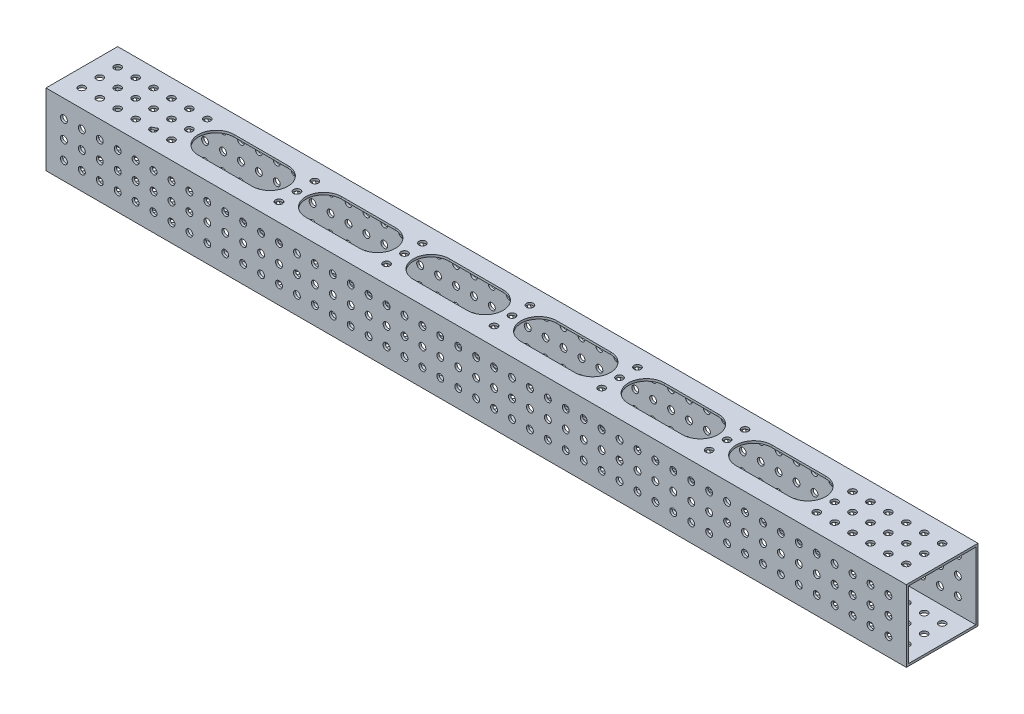
SolidWorks part; units mm, degrees
ref_plane "Front Plane" through (0, 0, 0) normal (0, 0, 1) x (1, 0, 0)
ref_plane "Top Plane" through (0, 0, 0) normal (0, 1, 0) x (1, 0, 0)
ref_plane "Right Plane" through (0, 0, 0) normal (1, 0, 0) x (0, 0, -1)
sketch "Sketch1" plane through (0, 0, 0) normal (1, 0, 0) x (0, 0, -1)
  line L1 (-25.4, -25.4) -> (25.4, -25.4)
  line L2 (-25.4, -25.4) -> (-25.4, 25.4)
  line L3 (-25.4, 25.4) -> (25.4, 25.4)
  line L4 (25.4, -25.4) -> (25.4, 25.4)
  line L5 (-25.4, -25.4) -> (25.4, 25.4) construction
  line L6 (-25.4, 25.4) -> (25.4, -25.4) construction
  line L7 (-23.8125, -23.8125) -> (23.8125, -23.8125)
  line L8 (-23.8125, -23.8125) -> (-23.8125, 23.8125)
  line L9 (-23.8125, 23.8125) -> (23.8125, 23.8125)
  line L10 (23.8125, -23.8125) -> (23.8125, 23.8125)
  line L11 (-23.8125, -23.8125) -> (23.8125, 23.8125) construction
  line L12 (-23.8125, 23.8125) -> (23.8125, -23.8125) construction
  point P0 (0, 0)
  point P7 (0, 0)
  dimension "D1" = 50.8
  dimension "D2" = 50.8
  dimension "D3" = 47.625
extrude "Boss-Extrude1" add sketch "Sketch1" along normal blind 609.6
sketch "Sketch2" plane through (0, 0, 25.4) normal (0, 0, 1) x (1, 0, 0)
  line L0 (-1000, 0) -> (49000, 0) construction
  line L2 (-994.1549, 12.7) -> (49005.8451, 12.7) construction
  line L3 (-984.8446, -12.7) -> (49015.1554, -12.7) construction
  line L4 (609.6, 25.4) -> (0, 25.4) construction
  line L5 (609.6, -25.4) -> (0, -25.4) construction
  line L6 (0, 25.4) -> (0, -25.4) construction
  line L7 (12.7, 12.7) -> (12.7, 0) construction
  line L8 (12.7, 12.7) -> (25.4, 12.7) construction
  circle A24 centre (12.7, 12.7) radius 2.4384
  circle A25 centre (12.7, 0) radius 2.4384
  circle A26 centre (12.7, -12.7) radius 2.4384
  circle A27 centre (25.4, 12.7) radius 2.4384
  circle A28 centre (25.4, 0) radius 2.4384
  circle A29 centre (25.4, -12.7) radius 2.4384
  circle A30 centre (38.1, 12.7) radius 2.4384
  circle A31 centre (38.1, 0) radius 2.4384
  circle A32 centre (38.1, -12.7) radius 2.4384
  circle A33 centre (50.8, 12.7) radius 2.4384
  circle A34 centre (50.8, 0) radius 2.4384
  circle A35 centre (50.8, -12.7) radius 2.4384
  circle A36 centre (63.5, 12.7) radius 2.4384
  circle A37 centre (63.5, 0) radius 2.4384
  circle A38 centre (63.5, -12.7) radius 2.4384
  circle A39 centre (76.2, 12.7) radius 2.4384
  circle A40 centre (76.2, 0) radius 2.4384
  circle A41 centre (76.2, -12.7) radius 2.4384
  circle A42 centre (88.9, 12.7) radius 2.4384
  circle A43 centre (88.9, 0) radius 2.4384
  circle A44 centre (88.9, -12.7) radius 2.4384
  circle A45 centre (101.6, 12.7) radius 2.4384
  circle A46 centre (101.6, 0) radius 2.4384
  circle A47 centre (101.6, -12.7) radius 2.4384
  circle A48 centre (114.3, 12.7) radius 2.4384
  circle A49 centre (114.3, 0) radius 2.4384
  circle A50 centre (114.3, -12.7) radius 2.4384
  circle A51 centre (127, 12.7) radius 2.4384
  circle A52 centre (127, 0) radius 2.4384
  circle A53 centre (127, -12.7) radius 2.4384
  circle A54 centre (139.7, 12.7) radius 2.4384
  circle A55 centre (139.7, 0) radius 2.4384
  circle A56 centre (139.7, -12.7) radius 2.4384
  circle A57 centre (152.4, 12.7) radius 2.4384
  circle A58 centre (152.4, 0) radius 2.4384
  circle A59 centre (152.4, -12.7) radius 2.4384
  circle A60 centre (165.1, 12.7) radius 2.4384
  circle A61 centre (165.1, 0) radius 2.4384
  circle A62 centre (165.1, -12.7) radius 2.4384
  circle A63 centre (177.8, 12.7) radius 2.4384
  circle A64 centre (177.8, 0) radius 2.4384
  circle A65 centre (177.8, -12.7) radius 2.4384
  circle A66 centre (190.5, 12.7) radius 2.4384
  circle A67 centre (190.5, 0) radius 2.4384
  circle A68 centre (190.5, -12.7) radius 2.4384
  circle A69 centre (203.2, 12.7) radius 2.4384
  circle A70 centre (203.2, 0) radius 2.4384
  circle A71 centre (203.2, -12.7) radius 2.4384
  circle A72 centre (215.9, 12.7) radius 2.4384
  circle A73 centre (215.9, 0) radius 2.4384
  circle A74 centre (215.9, -12.7) radius 2.4384
  circle A75 centre (228.6, 12.7) radius 2.4384
  circle A76 centre (228.6, 0) radius 2.4384
  circle A77 centre (228.6, -12.7) radius 2.4384
  circle A78 centre (241.3, 12.7) radius 2.4384
  circle A79 centre (241.3, 0) radius 2.4384
  circle A80 centre (241.3, -12.7) radius 2.4384
  circle A81 centre (254, 12.7) radius 2.4384
  circle A82 centre (254, 0) radius 2.4384
  circle A83 centre (254, -12.7) radius 2.4384
  circle A84 centre (266.7, 12.7) radius 2.4384
  circle A85 centre (266.7, 0) radius 2.4384
  circle A86 centre (266.7, -12.7) radius 2.4384
  circle A87 centre (279.4, 12.7) radius 2.4384
  circle A88 centre (279.4, 0) radius 2.4384
  circle A89 centre (279.4, -12.7) radius 2.4384
  circle A90 centre (292.1, 12.7) radius 2.4384
  circle A91 centre (292.1, 0) radius 2.4384
  circle A92 centre (292.1, -12.7) radius 2.4384
  circle A93 centre (304.8, 12.7) radius 2.4384
  circle A94 centre (304.8, 0) radius 2.4384
  circle A95 centre (304.8, -12.7) radius 2.4384
  circle A96 centre (317.5, 12.7) radius 2.4384
  circle A97 centre (317.5, 0) radius 2.4384
  circle A98 centre (317.5, -12.7) radius 2.4384
  circle A99 centre (330.2, 12.7) radius 2.4384
  circle A100 centre (330.2, 0) radius 2.4384
  circle A101 centre (330.2, -12.7) radius 2.4384
  circle A102 centre (342.9, 12.7) radius 2.4384
  circle A103 centre (342.9, 0) radius 2.4384
  circle A104 centre (342.9, -12.7) radius 2.4384
  circle A105 centre (355.6, 12.7) radius 2.4384
  circle A106 centre (355.6, 0) radius 2.4384
  circle A107 centre (355.6, -12.7) radius 2.4384
  circle A108 centre (368.3, 12.7) radius 2.4384
  circle A109 centre (368.3, 0) radius 2.4384
  circle A110 centre (368.3, -12.7) radius 2.4384
  circle A111 centre (381, 12.7) radius 2.4384
  circle A112 centre (381, 0) radius 2.4384
  circle A113 centre (381, -12.7) radius 2.4384
  circle A114 centre (393.7, 12.7) radius 2.4384
  circle A115 centre (393.7, 0) radius 2.4384
  circle A116 centre (393.7, -12.7) radius 2.4384
  circle A117 centre (406.4, 12.7) radius 2.4384
  circle A118 centre (406.4, 0) radius 2.4384
  circle A119 centre (406.4, -12.7) radius 2.4384
  circle A120 centre (419.1, 12.7) radius 2.4384
  circle A121 centre (419.1, 0) radius 2.4384
  circle A122 centre (419.1, -12.7) radius 2.4384
  circle A123 centre (431.8, 12.7) radius 2.4384
  circle A124 centre (431.8, 0) radius 2.4384
  circle A125 centre (431.8, -12.7) radius 2.4384
  circle A126 centre (444.5, 12.7) radius 2.4384
  circle A127 centre (444.5, 0) radius 2.4384
  circle A128 centre (444.5, -12.7) radius 2.4384
  circle A129 centre (457.2, 12.7) radius 2.4384
  circle A130 centre (457.2, 0) radius 2.4384
  circle A131 centre (457.2, -12.7) radius 2.4384
  circle A132 centre (469.9, 12.7) radius 2.4384
  circle A133 centre (469.9, 0) radius 2.4384
  circle A134 centre (469.9, -12.7) radius 2.4384
  circle A135 centre (482.6, 12.7) radius 2.4384
  circle A136 centre (482.6, 0) radius 2.4384
  circle A137 centre (482.6, -12.7) radius 2.4384
  circle A138 centre (495.3, 12.7) radius 2.4384
  circle A139 centre (495.3, 0) radius 2.4384
  circle A140 centre (495.3, -12.7) radius 2.4384
  circle A141 centre (508, 12.7) radius 2.4384
  circle A142 centre (508, 0) radius 2.4384
  circle A143 centre (508, -12.7) radius 2.4384
  circle A144 centre (520.7, 12.7) radius 2.4384
  circle A145 centre (520.7, 0) radius 2.4384
  circle A146 centre (520.7, -12.7) radius 2.4384
  circle A147 centre (533.4, 12.7) radius 2.4384
  circle A148 centre (533.4, 0) radius 2.4384
  circle A149 centre (533.4, -12.7) radius 2.4384
  circle A150 centre (546.1, 12.7) radius 2.4384
  circle A151 centre (546.1, 0) radius 2.4384
  circle A152 centre (546.1, -12.7) radius 2.4384
  circle A153 centre (558.8, 12.7) radius 2.4384
  circle A154 centre (558.8, 0) radius 2.4384
  circle A155 centre (558.8, -12.7) radius 2.4384
  circle A156 centre (571.5, 12.7) radius 2.4384
  circle A157 centre (571.5, 0) radius 2.4384
  circle A158 centre (571.5, -12.7) radius 2.4384
  circle A159 centre (584.2, 12.7) radius 2.4384
  circle A160 centre (584.2, 0) radius 2.4384
  circle A161 centre (584.2, -12.7) radius 2.4384
  circle A162 centre (596.9, 12.7) radius 2.4384
  circle A163 centre (596.9, 0) radius 2.4384
  circle A164 centre (596.9, -12.7) radius 2.4384
  dimension "D1" = 12.7
  dimension "D3" = 4.8768
  dimension "D2" = 12.7
  dimension "D4" = 12.7
  dimension "D6" = 12.7
  dimension "D8" = 12.7
  dimension "D5" = 3
  dimension "D7" = 47
extrude "Cut-Extrude2" cut sketch "Sketch2" against normal blind 609.6
sketch "Sketch3" plane through (0, -25.4, 0) normal (0, -1, 0) x (1, 0, 0)
  line L0 (0, 0) -> (6.35, 0)
  line L1 (76.2, 12.7) -> (63.5, 12.7) construction
  line L2 (0, 25.4) -> (0, -25.4) construction
  line L3 (19.05, 12.7) -> (57.15, 12.7)
  line L4 (19.05, -12.7) -> (57.15, -12.7)
  line L5 (609.6, 25.4) -> (0, 25.4) construction
  line L6 (95.25, 12.7) -> (133.35, 12.7)
  line L7 (95.25, -12.7) -> (133.35, -12.7)
  line L8 (171.45, 12.7) -> (209.55, 12.7)
  line L9 (171.45, -12.7) -> (209.55, -12.7)
  line L10 (247.65, 12.7) -> (285.75, 12.7)
  line L11 (247.65, -12.7) -> (285.75, -12.7)
  line L12 (323.85, 12.7) -> (361.95, 12.7)
  line L13 (323.85, -12.7) -> (361.95, -12.7)
  line L14 (400.05, 12.7) -> (438.15, 12.7)
  line L15 (400.05, -12.7) -> (438.15, -12.7)
  line L16 (476.25, 12.7) -> (514.35, 12.7)
  line L17 (476.25, -12.7) -> (514.35, -12.7)
  line L18 (552.45, 12.7) -> (590.55, 12.7)
  line L19 (552.45, -12.7) -> (590.55, -12.7)
  line L20 (535.8384, 0) -> (539.75, 0)
  line L21 (527.05, 0) -> (530.9616, 0)
  line L22 (383.4384, 0) -> (387.35, 0)
  line L23 (374.65, 0) -> (378.5616, 0)
  line L24 (459.6384, 0) -> (463.55, 0)
  line L25 (146.05, 0) -> (149.9616, 0)
  line L26 (222.25, 0) -> (226.1616, 0)
  line L27 (154.8384, 0) -> (158.75, 0)
  line L28 (307.2384, 0) -> (311.15, 0)
  line L29 (298.45, 0) -> (302.3616, 0)
  line L30 (231.0384, 0) -> (234.95, 0)
  line L31 (69.85, 0) -> (73.7616, 0)
  line L32 (78.6384, 0) -> (82.55, 0)
  line L33 (19.05, 12.7) -> (95.25, 12.7) construction
  arc A0 (19.05, 12.7) -> (19.05, -12.7) centre (19.05, 0) ccw
  arc A1 (57.15, -12.7) -> (57.15, 12.7) centre (57.15, 0) ccw
  circle A2 centre (76.2, 12.7) radius 2.4384
  circle A3 centre (76.2, 0) radius 2.4384
  circle A4 centre (76.2, -12.7) radius 2.4384
  arc A5 (95.25, 12.7) -> (95.25, -12.7) centre (95.25, 0) ccw
  arc A6 (133.35, -12.7) -> (133.35, 12.7) centre (133.35, 0) ccw
  circle A7 centre (152.4, 12.7) radius 2.4384
  circle A8 centre (152.4, 0) radius 2.4384
  circle A9 centre (152.4, -12.7) radius 2.4384
  arc A10 (171.45, 12.7) -> (171.45, -12.7) centre (171.45, 0) ccw
  arc A11 (209.55, -12.7) -> (209.55, 12.7) centre (209.55, 0) ccw
  circle A12 centre (228.6, 12.7) radius 2.4384
  circle A13 centre (228.6, 0) radius 2.4384
  circle A14 centre (228.6, -12.7) radius 2.4384
  arc A15 (247.65, 12.7) -> (247.65, -12.7) centre (247.65, 0) ccw
  arc A16 (285.75, -12.7) -> (285.75, 12.7) centre (285.75, 0) ccw
  circle A17 centre (304.8, 12.7) radius 2.4384
  circle A18 centre (304.8, 0) radius 2.4384
  circle A19 centre (304.8, -12.7) radius 2.4384
  arc A20 (323.85, 12.7) -> (323.85, -12.7) centre (323.85, 0) ccw
  arc A21 (361.95, -12.7) -> (361.95, 12.7) centre (361.95, 0) ccw
  circle A22 centre (381, 12.7) radius 2.4384
  circle A23 centre (381, 0) radius 2.4384
  circle A24 centre (381, -12.7) radius 2.4384
  arc A25 (400.05, 12.7) -> (400.05, -12.7) centre (400.05, 0) ccw
  arc A26 (438.15, -12.7) -> (438.15, 12.7) centre (438.15, 0) ccw
  circle A27 centre (457.2, 12.7) radius 2.4384
  circle A28 centre (457.2, 0) radius 2.4384
  circle A29 centre (457.2, -12.7) radius 2.4384
  arc A30 (476.25, 12.7) -> (476.25, -12.7) centre (476.25, 0) ccw
  arc A31 (514.35, -12.7) -> (514.35, 12.7) centre (514.35, 0) ccw
  circle A32 centre (533.4, 12.7) radius 2.4384
  circle A33 centre (533.4, 0) radius 2.4384
  circle A34 centre (533.4, -12.7) radius 2.4384
  arc A35 (552.45, 12.7) -> (552.45, -12.7) centre (552.45, 0) ccw
  arc A36 (590.55, -12.7) -> (590.55, 12.7) centre (590.55, 0) ccw
  circle A40 centre (609.6, 12.7) radius 2.4384 [skipped]
  circle A41 centre (609.6, 0) radius 2.4384 [skipped]
  circle A42 centre (609.6, -12.7) radius 2.4384 [skipped]
  circle A43 centre (546.1, 12.7) radius 2.4384
  circle A44 centre (546.1, 0) radius 2.4384
  circle A45 centre (546.1, -12.7) radius 2.4384
  circle A46 centre (558.8, 12.7) radius 2.4384
  circle A47 centre (558.8, 0) radius 2.4384
  circle A48 centre (558.8, -12.7) radius 2.4384
  circle A49 centre (571.5, 12.7) radius 2.4384
  circle A50 centre (571.5, 0) radius 2.4384
  circle A51 centre (571.5, -12.7) radius 2.4384
  circle A52 centre (584.2, 12.7) radius 2.4384
  circle A53 centre (584.2, 0) radius 2.4384
  circle A54 centre (584.2, -12.7) radius 2.4384
  circle A55 centre (596.9, 12.7) radius 2.4384
  circle A56 centre (596.9, 0) radius 2.4384
  circle A57 centre (596.9, -12.7) radius 2.4384
  circle A58 centre (63.5, 12.7) radius 2.4384
  circle A59 centre (63.5, -12.7) radius 2.4384
  circle A60 centre (63.5, 0) radius 2.4384
  circle A61 centre (50.8, 12.7) radius 2.4384
  circle A62 centre (50.8, -12.7) radius 2.4384
  circle A63 centre (50.8, 0) radius 2.4384
  circle A64 centre (38.1, 12.7) radius 2.4384
  circle A65 centre (38.1, -12.7) radius 2.4384
  circle A66 centre (38.1, 0) radius 2.4384
  circle A67 centre (25.4, 12.7) radius 2.4384
  circle A68 centre (25.4, -12.7) radius 2.4384
  circle A69 centre (25.4, 0) radius 2.4384
  circle A70 centre (12.7, 12.7) radius 2.4384
  circle A71 centre (12.7, -12.7) radius 2.4384
  circle A72 centre (12.7, 0) radius 2.4384
  dimension "D1" = 25.4
  dimension "D2" = 19.05
  dimension "D3" = 25.4
  dimension "D4" = 38.1
  dimension "D5" = 4.8768
  dimension ".2" = 4.8768
  dimension "D6" = 4.8768
  dimension "D8" = 12.7
  dimension "D9" = 12.7
  dimension "D10" = 76.2
  dimension "D11" = 76.2
  dimension "D12" = 76.2
  dimension "D7" = 12.7
  dimension "D15" = 76.2
  dimension "D16" = 6
  dimension "D17" = 12.7
  dimension "D18" = 12.7
  dimension "D13" = 8
  dimension "D14" = 6
extrude "Cut-Extrude3" cut sketch "Sketch3" against normal blind 76.2 contours L7 A6 L6 A5 | L9 A11 L8 A10 | L11 A16 L10 A15 | L13 A21 L12 A20 | A4 | A8 | A9 | A7 | A18 | A23 | L15 A26 L14 A25 | A28 | L17 A31 L16 A30 | A63 | A66 | A69 | A1 A58 | A2 | A3 | A12 | A13 | A14 | A17 | A19 | A22 | A24 | A27 | A29 | A33 | A32 | A34 | A62 | A61 | A64 | A65 | A68 | A67 | A70 | A72 | A71 | A60 | A59 | A45 | A48 | A51 | A44 | A43 | A46 | A49 | A52 | A53 | A50 | A47 | A54 | A57 | A56 | A55
